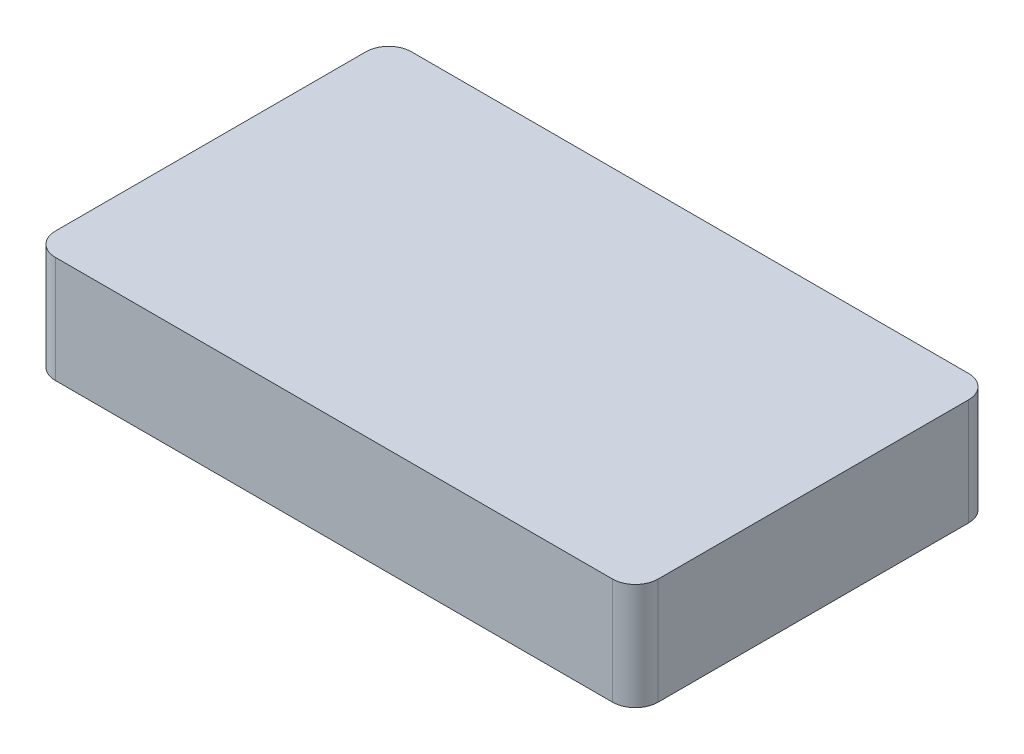
SolidWorks part; units mm, degrees
material "PBT General Purpose"
ref_plane "Front Plane" through (0, 0, 0) normal (0, 0, 1) x (1, 0, 0)
ref_plane "Top Plane" through (0, 0, 0) normal (0, 1, 0) x (1, 0, 0)
ref_plane "Right Plane" through (0, 0, 0) normal (1, 0, 0) x (0, 0, -1)
sketch "Sketch1" plane through (0, 0, 0) normal (0, 1, 0) x (1, 0, 0)
  line L1 (5, 0) -> (127.2, 0)
  line L2 (0, 5) -> (0, 73.1)
  line L3 (5, 78.1) -> (127.2, 78.1)
  line L4 (132.2, 5) -> (132.2, 73.1)
  line L5 (66.1, 78.1) -> (66.1, 0) construction
  line L6 (0, 39.05) -> (132.2, 39.05) construction
  arc A0 (127.2, 0) -> (132.2, 5) centre (127.2, 5) ccw
  arc A1 (127.2, 78.1) -> (132.2, 73.1) centre (127.2, 73.1) cw
  arc A2 (0, 73.1) -> (5, 78.1) centre (5, 73.1) cw
  arc A3 (5, 0) -> (0, 5) centre (5, 5) cw
  point P12 (0, 0)
  point P140 (66.1, 39.05)
  dimension "D1" = 5
  dimension "D2" = 78.1
  dimension "D3" = 132.2
extrude "Boss-Extrude1" add sketch "Sketch1" along normal blind 23.4
